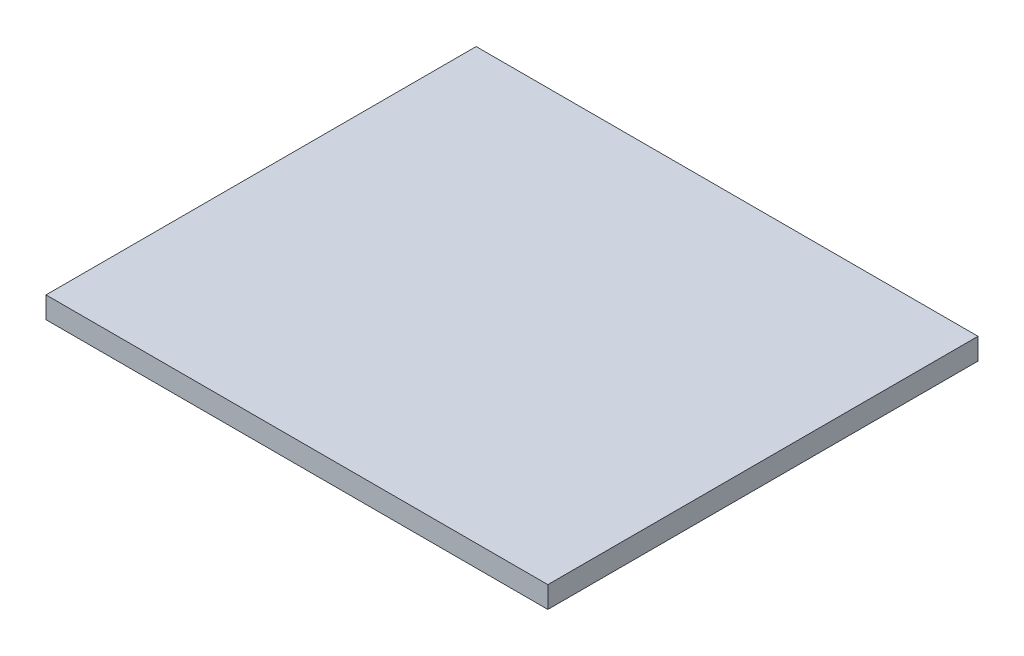
SolidWorks part; units mm, degrees
ref_plane "Plan de face" through (0, 0, 0) normal (0, 0, 1) x (1, 0, 0)
ref_plane "Plan de dessus" through (0, 0, 0) normal (0, 1, 0) x (1, 0, 0)
ref_plane "Plan de droite" through (0, 0, 0) normal (1, 0, 0) x (0, 0, -1)
sketch "Esquisse1" plane through (0, 0, 0) normal (0, 1, 0) x (1, 0, 0)
  line L1 (-35, -30) -> (35, -30)
  line L2 (-35, -30) -> (-35, 30)
  line L3 (-35, 30) -> (35, 30)
  line L4 (35, -30) -> (35, 30)
  line L5 (-35, -30) -> (35, 30) construction
  line L6 (-35, 30) -> (35, -30) construction
  point P0 (0, 0)
  dimension "D1" = 70
  dimension "D2" = 60
extrude "Boss.-Extru.1" add sketch "Esquisse1" along normal blind 3 contours L2 L3 L4 L1
